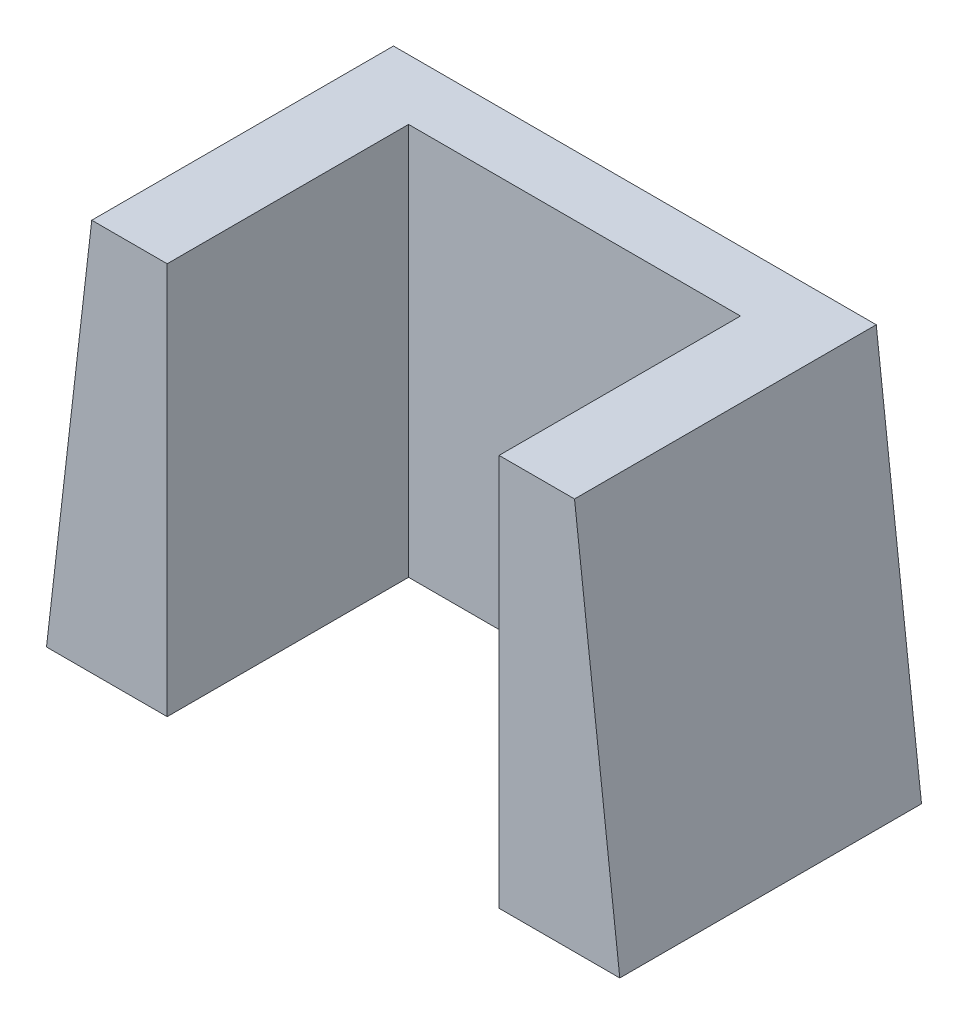
SolidWorks part; units mm, degrees
ref_plane "Спереди" through (0, 0, 0) normal (0, 0, 1) x (1, 0, 0)
ref_plane "Сверху" through (0, 0, 0) normal (0, 1, 0) x (1, 0, 0)
ref_plane "Справа" through (0, 0, 0) normal (1, 0, 0) x (0, 0, -1)
sketch "Эскиз1" plane through (0, 0, 0) normal (0, 0, 1) x (1, 0, 0)
  line L0 (-9.5, 0) -> (9.5, 0)
  line L1 (9.5, 0) -> (8, 13)
  line L2 (8, 13) -> (-8, 13)
  line L3 (-8, 13) -> (-9.5, 0)
  point P3 (0, 0)
  dimension "D1" = 19
  dimension "D2" = 16
  dimension "D3" = 13
extrude "Бобышка-Вытянуть1" add sketch "Эскиз1" along normal blind 10
sketch "Эскиз2" plane through (0, 13, 0) normal (0, 1, 0) x (1, 0, 0)
  line L1 (8, -10) -> (-8, -10) construction
  line L2 (-5.5, -10) -> (5.5, -10)
  line L3 (-5.5, -10) -> (-5.5, -2)
  line L4 (-5.5, -2) -> (5.5, -2)
  line L5 (5.5, -10) -> (5.5, -2)
  line L6 (0, 0) -> (0, -10) construction
  line L8 (8, 0) -> (-8, 0) construction
  point P6 (0, -2)
  dimension "D1" = 11
  dimension "D2" = 8
extrude "Вырез-Вытянуть1" cut sketch "Эскиз2" against normal through all
